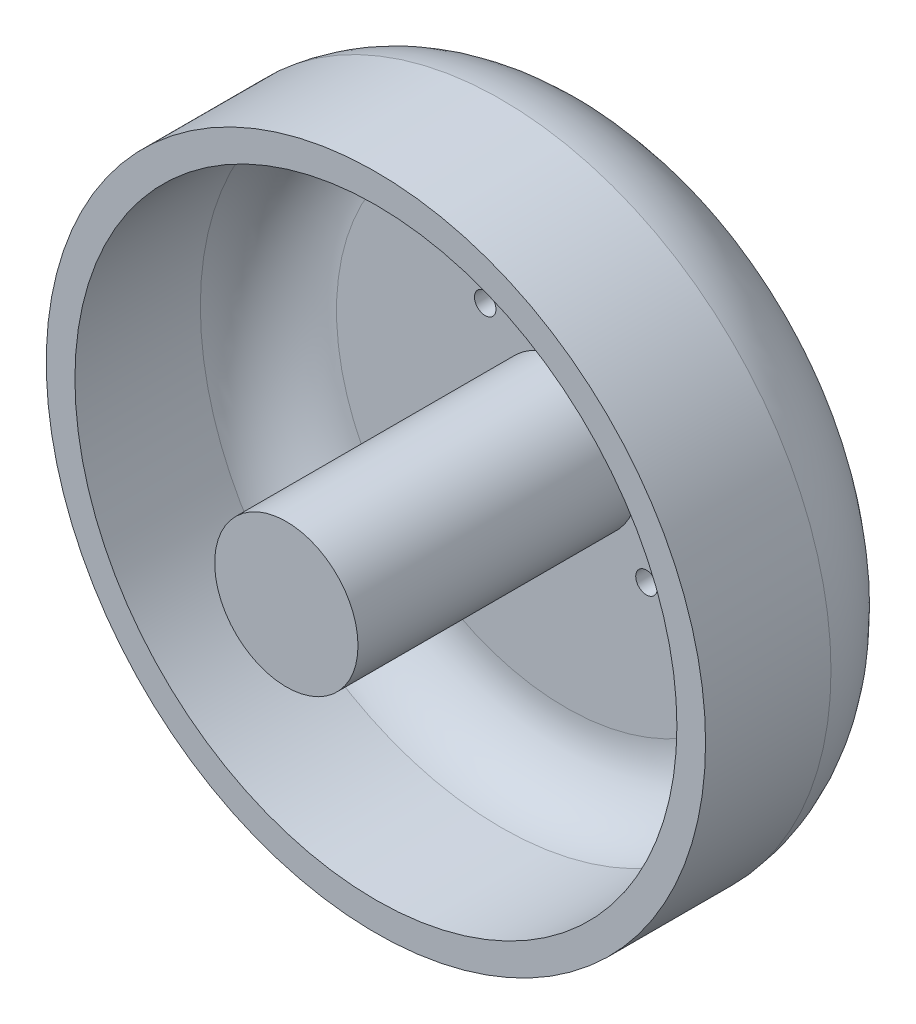
SolidWorks part; units mm, degrees
ref_plane "Front Plane" through (0, 0, 0) normal (0, 0, 1) x (1, 0, 0)
ref_plane "Top Plane" through (0, 0, 0) normal (0, 1, 0) x (1, 0, 0)
ref_plane "Right Plane" through (0, 0, 0) normal (1, 0, 0) x (0, 0, -1)
sketch "Sketch2" plane through (0, 0, 0) normal (1, 0, 0) x (0, 0, -1)
  line L0 (0, 0) -> (0, 32)
  line L2 (-6, 10) -> (-6, 32)
  line L3 (-15, 42) -> (-32.5, 42)
  line L4 (-32.5, 42) -> (-32.5, 46)
  line L5 (-32.5, 46) -> (-15, 46)
  line L6 (-677.9631, 0) -> (33220.1934, 0) construction
  line L8 (0, 0) -> (-45, 0)
  line L10 (-6, 10) -> (-45, 10)
  line L11 (-45, 0) -> (-45, 10)
  arc A0 (-15, 42) -> (-6, 32) centre (-15.9999, 32.0501) cw
  arc A1 (-15, 46) -> (0, 32) centre (-16.7491, 29.0902) cw
  dimension "D7" = 17
  dimension "D8" = 10
  dimension "D1" = 64
  dimension "D2" = 32.5
  dimension "D3" = 4
  dimension "D4" = 6
  dimension "D5" = 92
  dimension "D6" = 9
  dimension "D9" = 39
  dimension "D10" = 20
revolve "Body" add sketch "Sketch2" angle 360 about L6
sketch "Sketch3" plane through (0, 0, 0) normal (0, 0, -1) x (-1, 0, 0)
  line L1 (11.25, -11.25) -> (-11.25, -11.25) construction
  line L2 (11.25, -11.25) -> (11.25, 11.25) construction
  line L3 (11.25, 11.25) -> (-11.25, 11.25) construction
  line L4 (-11.25, -11.25) -> (-11.25, 11.25) construction
  line L5 (11.25, -11.25) -> (-11.25, 11.25) construction
  line L6 (11.25, 11.25) -> (-11.25, -11.25) construction
  circle A0 centre (-11.25, 11.25) radius 1.5
  circle A1 centre (11.25, 11.25) radius 1.5
  circle A2 centre (11.25, -11.25) radius 1.5
  circle A3 centre (-11.25, -11.25) radius 1.5
  point P0 (0, 0)
  dimension "D2" = 3
  dimension "D1" = 22.5
extrude "Fixation_Holes" cut sketch "Sketch3" against normal through all
sketch "Sketch4" plane through (0, 0, 0) normal (0, 0, -1) x (-1, 0, 0)
  circle A0 centre (0, 0) radius 1.5
  dimension "D1" = 3
extrude "Shaft" add sketch "Sketch4" along normal blind 6
